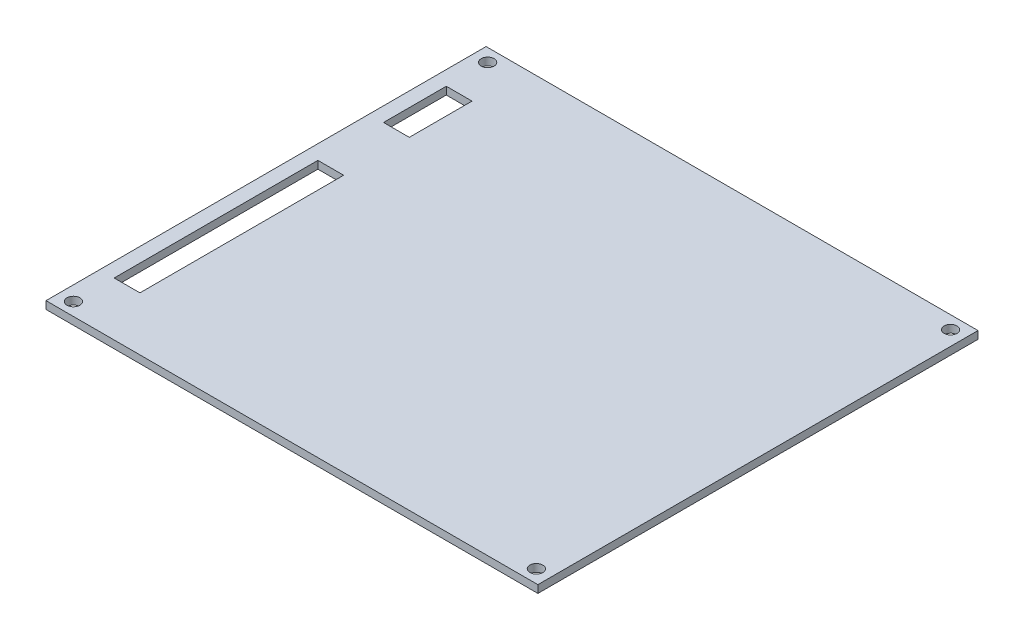
SolidWorks part; units mm, degrees
material "A-Glass Fiber"
ref_plane "Front Plane" through (0, 0, 0) normal (0, 0, 1) x (1, 0, 0)
ref_plane "Top Plane" through (0, 0, 0) normal (0, 1, 0) x (1, 0, 0)
ref_plane "Right Plane" through (0, 0, 0) normal (1, 0, 0) x (0, 0, -1)
sketch "Sketch1" plane through (0, 0, 0) normal (0, 1, 0) x (1, 0, 0)
  line L1 (48.26, -43.18) -> (-48.26, -43.18)
  line L2 (48.26, -43.18) -> (48.26, 43.18)
  line L3 (48.26, 43.18) -> (-48.26, 43.18)
  line L4 (-48.26, -43.18) -> (-48.26, 43.18)
  line L5 (48.26, -43.18) -> (-48.26, 43.18) construction
  line L6 (48.26, 43.18) -> (-48.26, -43.18) construction
  line L7 (-45.4212, 40.64) -> (45.4212, 40.64) construction
  line L8 (-45.4212, 40.64) -> (-45.4212, -40.64) construction
  line L9 (-45.4212, -40.64) -> (45.4212, -40.64) construction
  line L10 (45.4212, 40.64) -> (45.4212, -40.64) construction
  line L11 (-45.4212, 32.528) -> (-40.3688, 32.528)
  line L12 (-45.4212, 32.528) -> (-45.4212, 20.2142)
  line L13 (-45.4212, 20.2142) -> (-40.3688, 20.2142)
  line L14 (-40.3688, 32.528) -> (-40.3688, 20.2142)
  line L15 (-45.4212, 7.3321) -> (-40.3688, 7.3321)
  line L16 (-45.4212, 7.3321) -> (-45.4212, -32.6405)
  line L17 (-45.4212, -32.6405) -> (-40.3688, -32.6405)
  line L18 (-40.3688, 7.3321) -> (-40.3688, -32.6405)
  circle A0 centre (-45.4212, 40.64) radius 1.27
  circle A1 centre (45.4212, 40.64) radius 1.27
  circle A2 centre (-45.4212, -40.64) radius 1.27
  circle A3 centre (45.4212, -40.64) radius 1.27
  point P0 (0, 0)
  dimension "D3" = 2.54
  dimension "D1" = 86.36
  dimension "D2" = 96.52
  dimension "D4" = 2.54
extrude "Boss-Extrude1" add sketch "Sketch1" along normal blind 1.5
